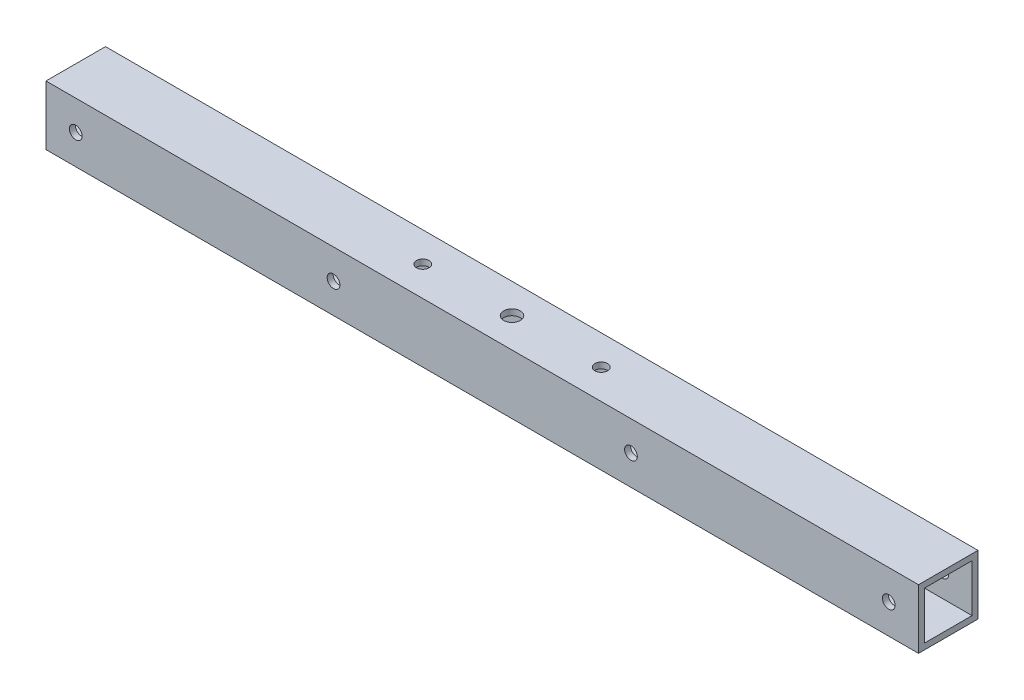
SolidWorks part; units mm, degrees
ref_plane "Front" through (0, 0, 0) normal (0, 0, 1) x (1, 0, 0)
ref_plane "Top" through (0, 0, 0) normal (0, 1, 0) x (1, 0, 0)
ref_plane "Right" through (0, 0, 0) normal (1, 0, 0) x (0, 0, -1)
sketch "ｽｹｯﾁ1" plane through (0, 0, 0) normal (1, 0, 0) x (0, 0, -1)
  line L0 (-6, 6) -> (-6, -6)
  line L1 (-7.5, 7.5) -> (7.5, 7.5)
  line L2 (-7.5, 7.5) -> (-7.5, -7.5)
  line L3 (-7.5, -7.5) -> (7.5, -7.5)
  line L4 (7.5, 7.5) -> (7.5, -7.5)
  line L5 (0, -7.5) -> (0, 7.5) construction
  line L6 (-7.5, 0) -> (7.5, 0) construction
  line L7 (-6, -6) -> (6, -6)
  line L8 (6, 6) -> (6, -6)
  line L9 (-6, 6) -> (6, 6)
  point P0 (0, 0)
  dimension "D1" = 15
  dimension "D2" = 15
  dimension "D3" = 1.5
extrude "ﾎﾞｽ - 押し出し1" add sketch "ｽｹｯﾁ1" along normal blind 220
sketch "ｽｹｯﾁ3" plane through (0, 0, 7.5) normal (0, 0, 1) x (1, 0, 0)
  line L0 (220, -7.5) -> (0, -7.5) construction
  line L1 (0, 7.5) -> (0, -7.5) construction
  line L2 (220, 7.5) -> (220, -7.5) construction
  line L3 (220, 7.5) -> (0, 7.5) construction
  circle A0 centre (7.5, 0) radius 1.6
  circle A1 centre (212.5, 0) radius 1.6
  circle A2 centre (72.5, 0) radius 1.6
  circle A3 centre (147.5, 0) radius 1.6
  point P14 (110, -7.5)
  dimension "D1" = 3.2
  dimension "D2" = 3.2
  dimension "D3" = 7.5
  dimension "D4" = 7.5
  dimension "D5" = 7.5
  dimension "D6" = 7.5
  dimension "D9" = 3.2
  dimension "D10" = 3.2
  dimension "D11" = 7.5
  dimension "D12" = 7.5
  dimension "D7" = 37.5
  dimension "D8" = 37.5
extrude "ｶｯﾄ - 押し出し2" cut sketch "ｽｹｯﾁ3" against normal through all
sketch "ｽｹｯﾁ4" plane through (0, 7.5, 0) normal (0, 1, 0) x (1, 0, 0)
  line L0 (220, -7.5) -> (0, -7.5) construction
  line L1 (0, 7.5) -> (0, -7.5) construction
  circle A0 centre (110, 0) radius 2.1
  circle A1 centre (132.5, 0) radius 1.6
  circle A2 centre (87.5, 0) radius 1.6
  dimension "D1" = 4.2
  dimension "D2" = 7.5
  dimension "D3" = 110
  dimension "D4" = 3.2
  dimension "D5" = 3.2
  dimension "D6" = 7.5
  dimension "D7" = 7.5
  dimension "D8" = 22.5
  dimension "D9" = 22.5
extrude "ｶｯﾄ - 押し出し3" cut sketch "ｽｹｯﾁ4" against normal through all
equation "\"２2。５\"= 14.0834"
